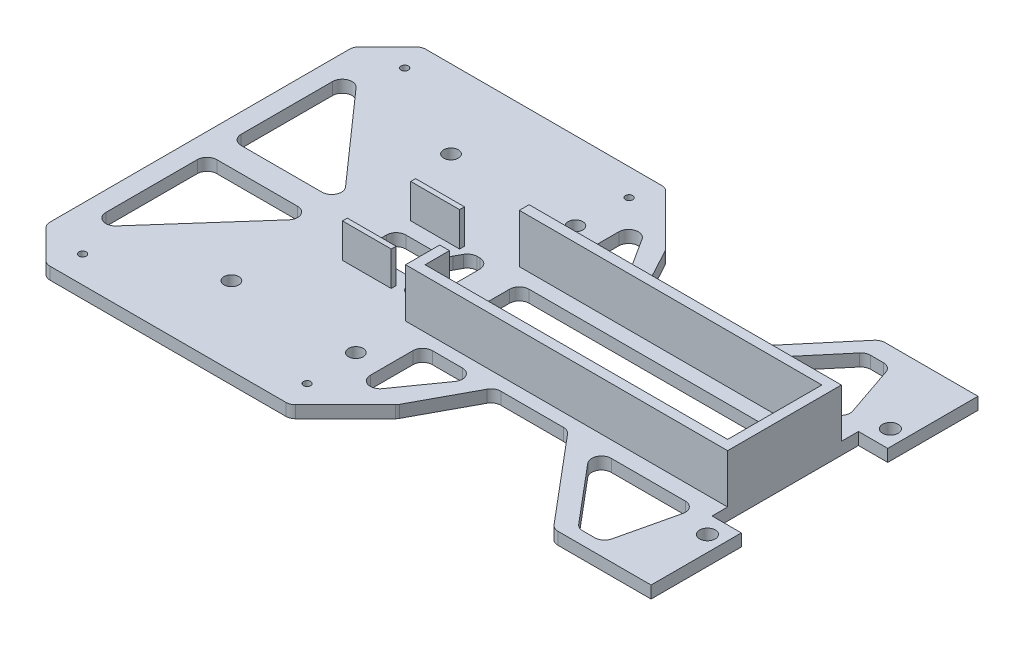
SolidWorks part; units mm, degrees
ref_plane "Front Plane" through (0, 0, 0) normal (0, 0, 1) x (1, 0, 0)
ref_plane "Top Plane" through (0, 0, 0) normal (0, 1, 0) x (1, 0, 0)
ref_plane "Right Plane" through (0, 0, 0) normal (1, 0, 0) x (0, 0, -1)
sketch "Sketch1" plane through (0, 0, 0) normal (0, 1, 0) x (1, 0, 0)
  line L1 (-10, 33.6838) -> (10, 33.6838)
  line L3 (-10, -33.3162) -> (10, -33.3162)
  line L4 (10, 33.6838) -> (10, -33.3162)
  line L5 (-26, 14.6838) -> (-41, 14.6838)
  line L6 (-26, -14.3162) -> (-41, -14.3162)
  line L8 (-26, 14.6838) -> (-10, 33.6838)
  line L11 (-26, -14.3162) -> (-10, -33.3162)
  line L18 (-48, 27.6838) -> (-41, 14.6838)
  line L19 (-48, -27.3162) -> (-41, -14.3162)
  line L23 (-59, 38.6838) -> (-48, 27.6838)
  line L25 (-59, -38.3162) -> (-48, -27.3162)
  line L27 (-59, 38.6838) -> (-109, 38.6838)
  line L29 (-59, -38.3162) -> (-109, -38.3162)
  line L32 (-116, 31.6838) -> (-109, 38.6838)
  line L33 (-116, 31.6838) -> (-116, -31.3162)
  line L36 (-109, -38.3162) -> (-116, -31.3162)
  point P0 (0, 0)
  dimension "D1" = 20
  dimension "D2" = 67
  dimension "D6" = 15
  dimension "D10" = 50
extrude "Boss-Extrude1" add sketch "Sketch1" along normal blind 2.5
sketch "Sketch2" plane through (0, 2.5, 0) normal (0, 1, 0) x (1, 0, 0)
  line L1 (10, 33.6838) -> (-10, 33.6838) construction
  line L3 (10, -33.3162) -> (10, 33.6838) construction
  circle A0 centre (6.8, 18.9338) radius 1.6
  circle A1 centre (6.8, -18.5662) radius 1.6
  dimension "D1" = 3.2
  dimension "D2" = 3.2
  dimension "D3" = 37.5
  dimension "D4" = 14.75
  dimension "D5" = 3.2
extrude "Cut-Extrude1" cut sketch "Sketch2" against normal blind 2.5
sketch "Sketch3" plane through (0, 2.5, 0) normal (0, 1, 0) x (1, 0, 0)
  line L1 (-109, -38.3162) -> (-59, -38.3162) construction
  circle A0 centre (-107, 33.1838) radius 0.75
  circle A1 centre (-61, 33.1838) radius 0.75
  circle A2 centre (-61, -32.8162) radius 0.75
  circle A3 centre (-107, -32.8162) radius 0.75
  dimension "D3" = 1.5
  dimension "D4" = 1.5
  dimension "D5" = 1.5
  dimension "D6" = 1.5
  dimension "D1" = 46
  dimension "D2" = 46
  dimension "D7" = 66
  dimension "D8" = 5.5
  dimension "D9" = 2
  dimension "D10" = 2
extrude "Cut-Extrude2" cut sketch "Sketch3" against normal blind 2.5
sketch "Sketch4" plane through (0, 2.5, 0) normal (0, 1, 0) x (1, 0, 0)
  line L0 (10, -33.3162) -> (10, 33.6838) construction
  line L1 (10, 15.1838) -> (4, 15.1838)
  line L2 (10, 15.1838) -> (10, -14.8162)
  line L3 (10, -14.8162) -> (4, -14.8162)
  line L4 (4, 15.1838) -> (4, -14.8162)
  circle A0 centre (6.8, 18.9338) radius 1.6 construction
  dimension "D3" = 3.75
  dimension "D1" = 30
  dimension "D2" = 6
extrude "Cut-Extrude3" cut sketch "Sketch4" against normal blind 10
sketch "Sketch5" plane through (0, 2.5, 0) normal (0, 1, 0) x (1, 0, 0)
  line L1 (-59, 38.6838) -> (-109, 38.6838) construction
  line L2 (-109, -38.3162) -> (-59, -38.3162) construction
  line L3 (-116, 31.6838) -> (-116, -31.3162) construction
  circle A0 centre (-87, 22.6838) radius 1.5
  circle A1 centre (-61.5, 22.6838) radius 1.5
  circle A2 centre (-61.5, -22.3162) radius 1.5
  circle A3 centre (-87, -22.3162) radius 1.5
  dimension "D1" = 3
  dimension "D2" = 3
  dimension "D3" = 3
  dimension "D4" = 3
  dimension "D5" = 25.5
  dimension "D6" = 25.5
  dimension "D7" = 16
  dimension "D8" = 16
  dimension "D9" = 29
  dimension "D10" = 29
extrude "Cut-Extrude4" cut sketch "Sketch5" against normal blind 10
sketch "Sketch6" plane through (0, 2.5, 0) normal (0, 1, 0) x (1, 0, 0)
  line L0 (4, 15.1838) -> (4, -14.8162) construction
  line L7 (4, -11.6313) -> (-62, -11.6313)
  line L8 (-62, -11.6313) -> (-62, -4.6313)
  line L9 (4, 11.6838) -> (-60, 11.6838)
  line L10 (-62, -4.6313) -> (-60, -4.6313)
  line L11 (-60, 11.6838) -> (-60, 9.6838)
  line L12 (4, 11.6838) -> (4, -11.6313)
  line L13 (-60, 9.6838) -> (2, 9.6838)
  line L14 (2, 9.6838) -> (2, -9.6313)
  line L15 (2, -9.6313) -> (-60, -9.6313)
  line L16 (-60, -9.6313) -> (-60, -4.6313)
  dimension "D1" = 2
  dimension "D2" = 64
  dimension "D3" = 2
  dimension "D5" = 66
  dimension "D6" = 7
extrude "Boss-Extrude2" add sketch "Sketch6" along normal blind 10
sketch "Sketch7" plane through (0, 2.5, 0) normal (0, 1, 0) x (1, 0, 0)
  line L0 (-109, -38.3162) -> (-59, -38.3162) construction
  line L1 (-69.25, 7.6838) -> (-79.25, 7.6838)
  line L2 (-69.25, 7.6838) -> (-69.25, 6.6838)
  line L3 (-69.25, 6.6838) -> (-79.25, 6.6838)
  line L4 (-79.25, 7.6838) -> (-79.25, 6.6838)
  line L5 (-79.25, -6.3162) -> (-69.25, -6.3162)
  line L6 (-79.25, -6.3162) -> (-79.25, -7.3162)
  line L7 (-79.25, -7.3162) -> (-69.25, -7.3162)
  line L8 (-69.25, -6.3162) -> (-69.25, -7.3162)
  line L9 (-59, 38.6838) -> (-109, 38.6838) construction
  circle A0 centre (-87, -22.3162) radius 1.5 construction
  circle A2 centre (-87, 22.6838) radius 1.5 construction
  dimension "D7" = 7.75
  dimension "D8" = 7.75
  dimension "D1" = 1
  dimension "D2" = 1
  dimension "D3" = 31
  dimension "D4" = 31
  dimension "D5" = 10
  dimension "D6" = 10
extrude "Boss-Extrude3" add sketch "Sketch7" along normal blind 7
sketch "Sketch8" plane through (0, 2.5, 0) normal (0, 1, 0) x (1, 0, 0)
  line L0 (-60, 9.6838) -> (2, 9.6838) construction
  line L1 (-57, 6.6838) -> (-1, 6.6838)
  line L2 (-57, 6.6838) -> (-57, -6.6313)
  line L3 (-57, -6.6313) -> (-1, -6.6313)
  line L4 (-1, 6.6838) -> (-1, -6.6313)
  line L5 (2, -9.6313) -> (-60, -9.6313) construction
  line L6 (2, 9.6838) -> (2, -9.6313) construction
  line L7 (-60, -9.6313) -> (-60, -4.6313) construction
  dimension "D1" = 3
  dimension "D2" = 3
  dimension "D3" = 3
  dimension "D4" = 3
extrude "Cut-Extrude5" cut sketch "Sketch8" against normal blind 7
fillet "Fillet1" radius 2 14 edges at (-116, 1.25, -31.6838) (-109, 1.25, -38.6838) (-59, 1.25, -38.6838) (-10, 1.25, -33.6838) (-26, 1.25, -14.6838) (-41, 1.25, -14.6838) (-48, 1.25, -27.6838) (-10, 1.25, 33.3162) (-26, 1.25, 14.3162) (-41, 1.25, 14.3162) (-59, 1.25, 38.3162) (-48, 1.25, 27.3162) (-116, 1.25, 31.3162) (-109, 1.25, 38.3162)
sketch "Sketch9" plane through (0, 2.5, 0) normal (0, 1, 0) x (1, 0, 0)
  line L0 (-79.25, 3.6838) -> (-79.25, -3.3162)
  line L1 (-79.25, -3.3162) -> (-69.25, -3.3162)
  line L2 (-69.25, -3.3162) -> (-67.3582, -6.8162)
  line L3 (-67.3582, -6.8162) -> (-63.6082, -6.8162)
  line L4 (-63.6082, -6.8162) -> (-63.6082, 7.1838)
  line L5 (-63.6082, 7.1838) -> (-67.3582, 7.1838)
  line L6 (-67.3582, 7.1838) -> (-69.25, 3.6838)
  line L7 (-69.25, 3.6838) -> (-79.25, 3.6838)
  line L8 (-79.25, 6.6838) -> (-69.25, 6.6838) construction
  line L10 (-79.25, 7.6838) -> (-79.25, 6.6838) construction
  dimension "D1" = 7
  dimension "D2" = 3
  dimension "D3" = 0
  dimension "D4" = 10
  dimension "D5" = 10
  dimension "D6" = 14
  dimension "D7" = 3.5
  dimension "D8" = 3.75
  dimension "D9" = 3.75
extrude "Cut-Extrude6" cut sketch "Sketch9" against normal blind 7
fillet "Fillet3" radius 2 8 edges at (-79.25, 1.25, 3.3162) (-79.25, 1.25, -3.6838) (-67.3582, 1.25, -7.1838) (-67.3582, 1.25, 6.8162) (-69.25, 1.25, 3.3162) (-69.25, 1.25, -3.6838) (-63.6082, 1.25, -7.1838) (-63.6082, 1.25, 6.8162)
sketch "Sketch10" plane through (0, 2.5, 0) normal (0, 1, 0) x (1, 0, 0)
  line L0 (-44, -14.1313) -> (-56, -14.1313)
  line L1 (-56, -14.1313) -> (-56, -31.1404)
  line L2 (-56, -31.1404) -> (-44, -14.1313)
  line L3 (-44, 14.1838) -> (-56, 14.1838)
  line L4 (-56, 14.1838) -> (-56, 32.8918)
  line L5 (-56, 32.8918) -> (-44, 14.1838)
  line L6 (-62, -11.6313) -> (4, -11.6313) construction
  line L7 (4, 11.6838) -> (-60, 11.6838) construction
  line L8 (-60, 11.6838) -> (-60, 9.6838) construction
  line L9 (-60, -9.6313) -> (-60, -4.6313) construction
  point P14 (-60, -7.1313)
  dimension "D1" = 12
  dimension "D2" = 2.5
  dimension "D3" = 12
  dimension "D4" = 2.5
  dimension "D5" = 4
  dimension "D6" = 4
extrude "Cut-Extrude7" cut sketch "Sketch10" against normal blind 7
fillet "Fillet6" radius 2 6 edges at (-56, 1.25, -32.8918) (-44, 1.25, -14.1838) (-56, 1.25, -14.1838) (-56, 1.25, 14.1313) (-56, 1.25, 31.1404) (-44, 1.25, 14.1313)
sketch "Sketch11" plane through (0, 2.5, 0) normal (0, 1, 0) x (1, 0, 0)
  line L0 (-4.2203, 29.9523) -> (-9.2203, 29.9523)
  line L1 (-9.2203, 29.9523) -> (-21.3144, 15.5906)
  line L2 (-21.3144, 15.5906) -> (0.6856, 15.5906)
  line L3 (0.6856, 15.5906) -> (-4.2203, 29.9523)
  line L4 (-20.8612, -14.9111) -> (1.1388, -14.9111)
  line L5 (1.1388, -14.9111) -> (-2.5636, -30.7021)
  line L6 (-2.5636, -30.7021) -> (-7.5636, -30.7021)
  line L7 (-7.5636, -30.7021) -> (-20.8612, -14.9111)
  line L8 (-10.5994, 32.9721) -> (-25.4006, 15.3955) construction
  line L10 (-25.4006, -15.0279) -> (-10.5994, -32.6045) construction
  dimension "D1" = 5
  dimension "D2" = 3
  dimension "D3" = 22
  dimension "D4" = 22
  dimension "D5" = 5
  dimension "D6" = 0
  dimension "D7" = 15.791
  dimension "D8" = 0
extrude "Cut-Extrude8" cut sketch "Sketch11" against normal blind 7
fillet "Fillet7" radius 2 8 edges at (-4.2203, 1.25, -29.9523) (-9.2203, 1.25, -29.9523) (-21.3144, 1.25, -15.5906) (0.6856, 1.25, -15.5906) (-2.5636, 1.25, 30.7021) (-7.5636, 1.25, 30.7021) (1.1388, 1.25, 14.9111) (-20.8612, 1.25, 14.9111)
sketch "Sketch12" plane through (0, 2.5, 0) normal (0, 1, 0) x (1, 0, 0)
  line L0 (-112, 28.6838) -> (-112, 2.6838)
  line L1 (-112, -2.3162) -> (-112, -28.3162)
  line L2 (-112, -28.3162) -> (-89, -2.3162)
  line L3 (-89, -2.3162) -> (-112, -2.3162)
  line L4 (-112, 2.6838) -> (-89, 2.6838)
  line L5 (-89, 2.6838) -> (-112, 28.6838)
  line L6 (-116, 30.8554) -> (-116, -30.4878) construction
  line L7 (-70.4424, 3.6838) -> (-77.25, 3.6838) construction
  line L8 (-77.25, -3.3162) -> (-70.4424, -3.3162) construction
  dimension "D1" = 4
  dimension "D2" = 1
  dimension "D3" = 1
  dimension "D4" = 26
  dimension "D5" = 26
  dimension "D6" = 23
  dimension "D7" = 23
extrude "Cut-Extrude9" cut sketch "Sketch12" against normal blind 7
fillet "Fillet8" radius 2 6 edges at (-112, 1.25, 28.3162) (-112, 1.25, -2.6838) (-112, 1.25, 2.3162) (-112, 1.25, -28.6838) (-89, 1.25, -2.6838) (-89, 1.25, 2.3162)
fillet "Fillet9" radius 2 4 edges at (-1, 1.25, -6.6838) (-57, 1.25, -6.6838) (-57, 1.25, 6.6313) (-1, 1.25, 6.6313)
